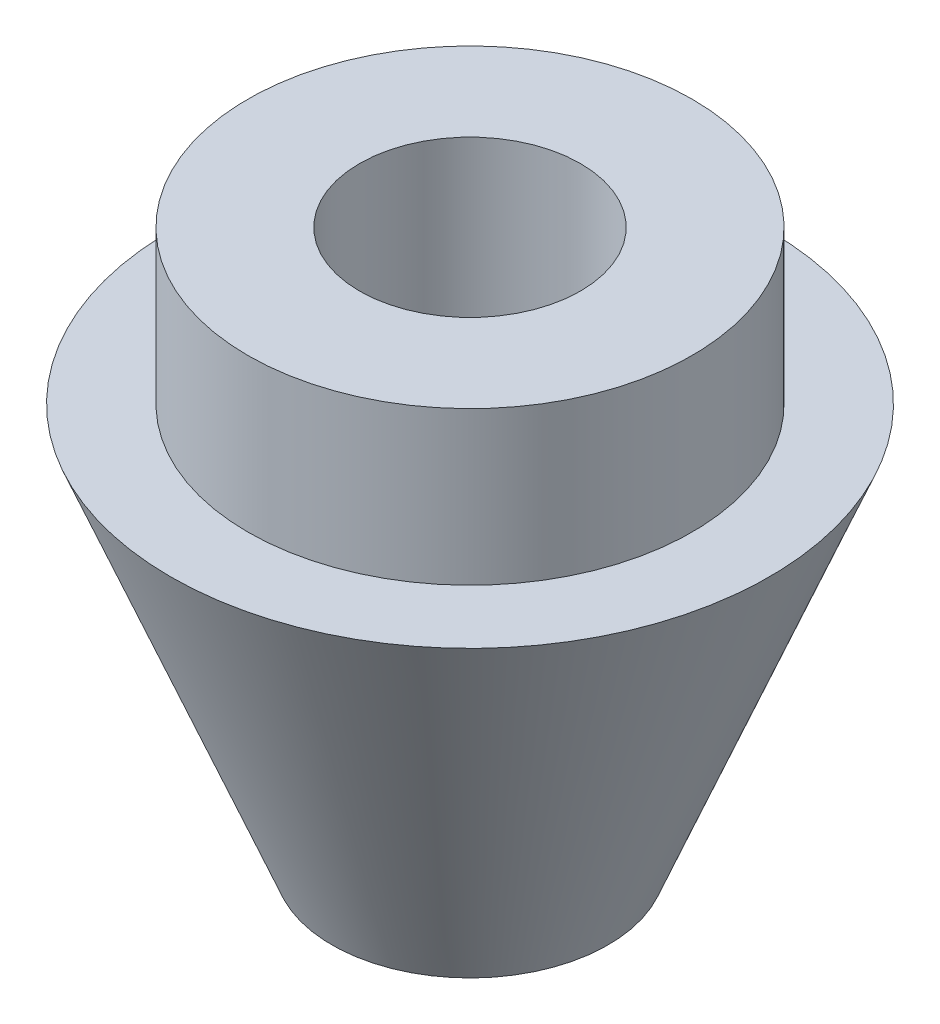
SolidWorks part; units mm, degrees
material "AISI 316 Stainless Steel Sheet (SS)"
ref_plane "Front Plane" through (0, 0, 0) normal (0, 0, 1) x (1, 0, 0)
ref_plane "Top Plane" through (0, 0, 0) normal (0, 1, 0) x (1, 0, 0)
ref_plane "Right Plane" through (0, 0, 0) normal (1, 0, 0) x (0, 0, -1)
sketch "Sketch1" plane through (0, 0, 0) normal (0, 0, 1) x (1, 0, 0)
  line L0 (0, 0) -> (0, 12.7)
  line L1 (0, 12.7) -> (-5.1054, 12.7)
  line L2 (-5.1054, 12.7) -> (-5.1054, 9.1838)
  line L3 (-5.1054, 9.1838) -> (-6.8834, 9.1838)
  line L4 (-6.8834, 9.1838) -> (-3.175, 0)
  line L5 (-3.175, 0) -> (0, 0)
  dimension "D1" = 12.7
  dimension "D2" = 9.1838
  dimension "D3" = 1.778
  dimension "D4" = 3.175
  dimension "D5" = 5.1054
revolve "Revolve1" add sketch "Sketch1" angle 360 about L0
sketch "]" plane through (0, 12.7, 0) normal (0, 1, 0) x (1, 0, 0)
  circle A0 centre (0, 0) radius 2.54
  circle A1 centre (0, 0) radius 2.54
  dimension "D1" = 5.08
extrude "Cut-Extrude4" cut sketch "]" against normal blind 12.7 contours A0
